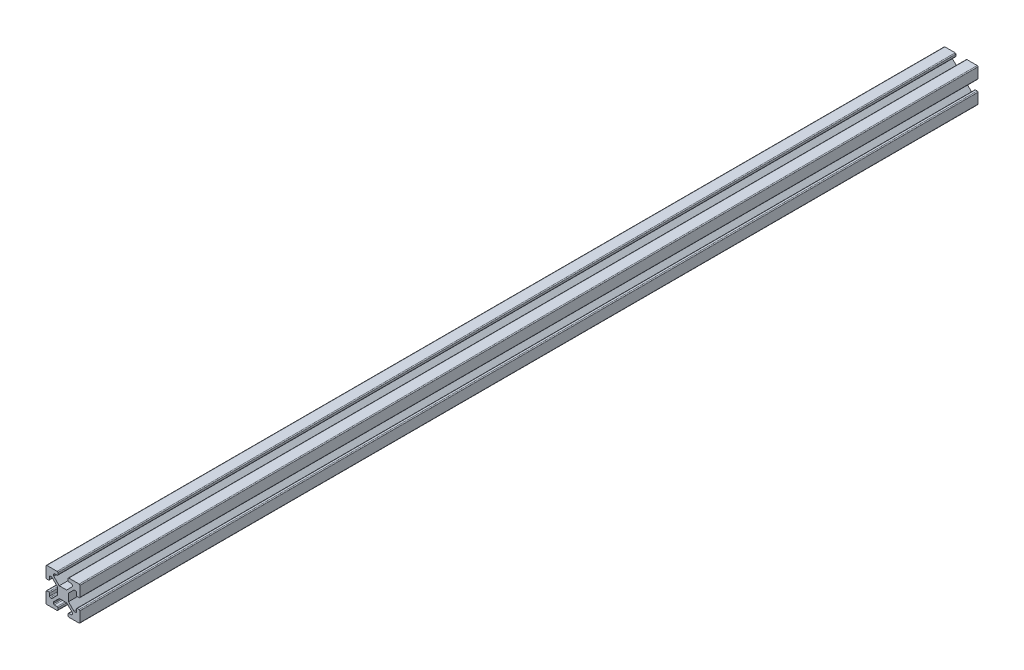
SolidWorks part; units mm, degrees
material "3.1645 (EN AW-2007)"
ref_plane "Front" through (0, 0, 0) normal (0, 0, 1) x (1, 0, 0)
ref_plane "Top" through (0, 0, 0) normal (0, 1, 0) x (1, 0, 0)
ref_plane "Right" through (0, 0, 0) normal (1, 0, 0) x (0, 0, -1)
sketch "草图1" plane through (0, 0, 0) normal (0, 0, 1) x (1, 0, 0)
  line L0 (6.5, 0) -> (0.5, 0)
  line L1 (20, -0.5) -> (20, -6.5)
  line L2 (19.5, -20) -> (13.5, -20)
  line L3 (20, -13.5) -> (20, -19.5)
  line L4 (13, -19.5) -> (13, -18.5)
  line L5 (13.5, -18) -> (15, -18)
  line L6 (15.5, -17.5) -> (15.5, -16.7791)
  line L7 (19.5, -7) -> (18.5, -7)
  line L8 (10, 0) -> (10, -26.2948) construction
  line L9 (18, -6.5) -> (18, -5)
  line L10 (17.5, -4.5) -> (16.7791, -4.5)
  line L11 (17.5, -15.5) -> (16.7791, -15.5)
  line L12 (18, -13.5) -> (18, -15)
  line L13 (19.5, -13) -> (18.5, -13)
  line L15 (0, -10) -> (20, -10) construction
  line L23 (4.5, -17.5) -> (4.5, -16.7791)
  line L24 (6.5, -18) -> (5, -18)
  line L25 (7, -19.5) -> (7, -18.5)
  line L27 (0.5, -20) -> (6.5, -20)
  line L29 (10, -20) -> (10, 6.2948) construction
  line L33 (0.5, -13) -> (1.5, -13)
  line L34 (2, -13.5) -> (2, -15)
  line L35 (2.5, -15.5) -> (3.2209, -15.5)
  line L36 (2.5, -4.5) -> (3.2209, -4.5)
  line L37 (2, -6.5) -> (2, -5)
  line L38 (0.5, -7) -> (1.5, -7)
  line L40 (7, -0.5) -> (7, -1.5)
  line L41 (6.5, -2) -> (5, -2)
  line L42 (4.5, -2.5) -> (4.5, -3.2209)
  line L43 (3.5745, -4.6464) -> (6.7416, -7.8136)
  line L44 (6.7416, -7.8136) -> (6.7416, -12.1864)
  line L45 (15.5, -2.5) -> (15.5, -3.2209)
  line L46 (13.5, -2) -> (15, -2)
  line L47 (13, -0.5) -> (13, -1.5)
  line L48 (19.5, 0) -> (13.5, 0)
  line L50 (10.3536, -10.3536) -> (20, -20) construction
  line L51 (4.6464, -3.5745) -> (7.8136, -6.7416)
  line L52 (7.8136, -6.7416) -> (12.1864, -6.7416)
  line L53 (0, -20) -> (9.6464, -10.3536) construction
  line L54 (15.3536, -3.5745) -> (12.1864, -6.7416)
  line L55 (13.2584, -7.8136) -> (13.2584, -12.1864)
  line L56 (16.4255, -4.6464) -> (13.2584, -7.8136)
  line L57 (10, 0) -> (10, -26.2948) construction
  line L58 (10, -20) -> (10, 6.2948) construction
  line L59 (16.4255, -15.3536) -> (13.2584, -12.1864)
  line L60 (15.3536, -16.4255) -> (12.3328, -13.4048)
  line L61 (8.0207, -13.2584) -> (11.9793, -13.2584)
  line L62 (4.6464, -16.4255) -> (7.6672, -13.4048)
  line L63 (3.5745, -15.3536) -> (6.7416, -12.1864)
  line L64 (0, -6.5) -> (0, -0.5)
  line L66 (0, -13.5) -> (0, -19.5)
  arc A0 (19.5, -7) -> (20, -6.5) centre (19.5, -6.5) ccw
  arc A1 (4.6464, -16.4255) -> (4.5, -16.7791) centre (5, -16.7791) ccw
  arc A2 (8.0207, -13.2584) -> (7.6672, -13.4048) centre (8.0207, -13.7584) ccw
  arc A3 (12.3328, -13.4048) -> (11.9793, -13.2584) centre (11.9793, -13.7584) ccw
  arc A4 (16.4255, -15.3536) -> (16.7791, -15.5) centre (16.7791, -15) ccw
  arc A5 (16.4255, -4.6464) -> (16.7791, -4.5) centre (16.7791, -5) cw
  arc A6 (15.3536, -16.4255) -> (15.5, -16.7791) centre (15, -16.7791) cw
  arc A7 (10.3536, -10.3536) -> (9.6464, -10.3536) centre (10, -10.7071) ccw construction
  arc A8 (15.3536, -3.5745) -> (15.5, -3.2209) centre (15, -3.2209) ccw
  arc A9 (3.5745, -15.3536) -> (3.2209, -15.5) centre (3.2209, -15) cw
  arc A10 (3.5745, -4.6464) -> (3.2209, -4.5) centre (3.2209, -5) ccw
  arc A11 (0.5, -7) -> (0, -6.5) centre (0.5, -6.5) cw
  arc A12 (2, -6.5) -> (1.5, -7) centre (1.5, -6.5) cw
  arc A13 (4.6464, -3.5745) -> (4.5, -3.2209) centre (5, -3.2209) cw
  arc A14 (2.5, -4.5) -> (2, -5) centre (2.5, -5) ccw
  arc A15 (2, -15) -> (2.5, -15.5) centre (2.5, -15) ccw
  arc A16 (1.5, -13) -> (2, -13.5) centre (1.5, -13.5) cw
  arc A17 (0.5, -13) -> (0, -13.5) centre (0.5, -13.5) ccw
  arc A18 (19.5, -13) -> (20, -13.5) centre (19.5, -13.5) cw
  arc A19 (13.5, 0) -> (13, -0.5) centre (13.5, -0.5) ccw
  arc A20 (13, -1.5) -> (13.5, -2) centre (13.5, -1.5) ccw
  arc A21 (15, -2) -> (15.5, -2.5) centre (15, -2.5) cw
  arc A22 (18, -13.5) -> (18.5, -13) centre (18.5, -13.5) cw
  arc A23 (4.5, -2.5) -> (5, -2) centre (5, -2.5) cw
  arc A24 (6.5, -2) -> (7, -1.5) centre (6.5, -1.5) ccw
  arc A25 (7, -0.5) -> (6.5, 0) centre (6.5, -0.5) ccw
  arc A26 (6.5, -18) -> (7, -18.5) centre (6.5, -18.5) cw
  arc A27 (4.5, -17.5) -> (5, -18) centre (5, -17.5) ccw
  arc A28 (17.5, -15.5) -> (18, -15) centre (17.5, -15) ccw
  arc A29 (15, -18) -> (15.5, -17.5) centre (15, -17.5) ccw
  arc A30 (13, -18.5) -> (13.5, -18) centre (13.5, -18.5) cw
  arc A31 (18, -5) -> (17.5, -4.5) centre (17.5, -5) ccw
  arc A32 (18.5, -7) -> (18, -6.5) centre (18.5, -6.5) cw
  arc A33 (19.5, 0) -> (20, -0.5) centre (19.5, -0.5) cw
  arc A34 (0.5, 0) -> (0, -0.5) centre (0.5, -0.5) ccw
  arc A35 (7, -19.5) -> (6.5, -20) centre (6.5, -19.5) cw
  arc A36 (13.5, -20) -> (13, -19.5) centre (13.5, -19.5) cw
  arc A37 (0.5, -20) -> (0, -19.5) centre (0.5, -19.5) cw
  arc A38 (20, -19.5) -> (19.5, -20) centre (19.5, -19.5) cw
  point P28 (4.5, -16.572)
  point P50 (10, -6.7416)
  point P56 (13.2584, -10)
  point P61 (6.7416, -10)
  point P62 (10, -13.2584)
  point P63 (7.8136, -13.2584)
  point P66 (12.1864, -13.2584)
  point P69 (16.572, -15.5)
  point P72 (16.572, -4.5)
  point P75 (15.5, -16.572)
  point P78 (10, -10)
  point P81 (15.5, -3.428)
  point P84 (3.428, -15.5)
  point P87 (3.428, -4.5)
  point P94 (4.5, -3.428)
  point P107 (13, 0)
  point P110 (13, -2)
  point P113 (15.5, -2)
  point P118 (4.5, -2)
  point P121 (7, -2)
  point P124 (7, 0)
  point P127 (7, -18)
  point P130 (4.5, -18)
  point P135 (15.5, -18)
  point P138 (13, -18)
  point P145 (20, 0)
  point P148 (0, 0)
  point P151 (7, -20)
  point P154 (13, -20)
extrude "凸台-拉伸1" add sketch "草图1" along normal blind 530
